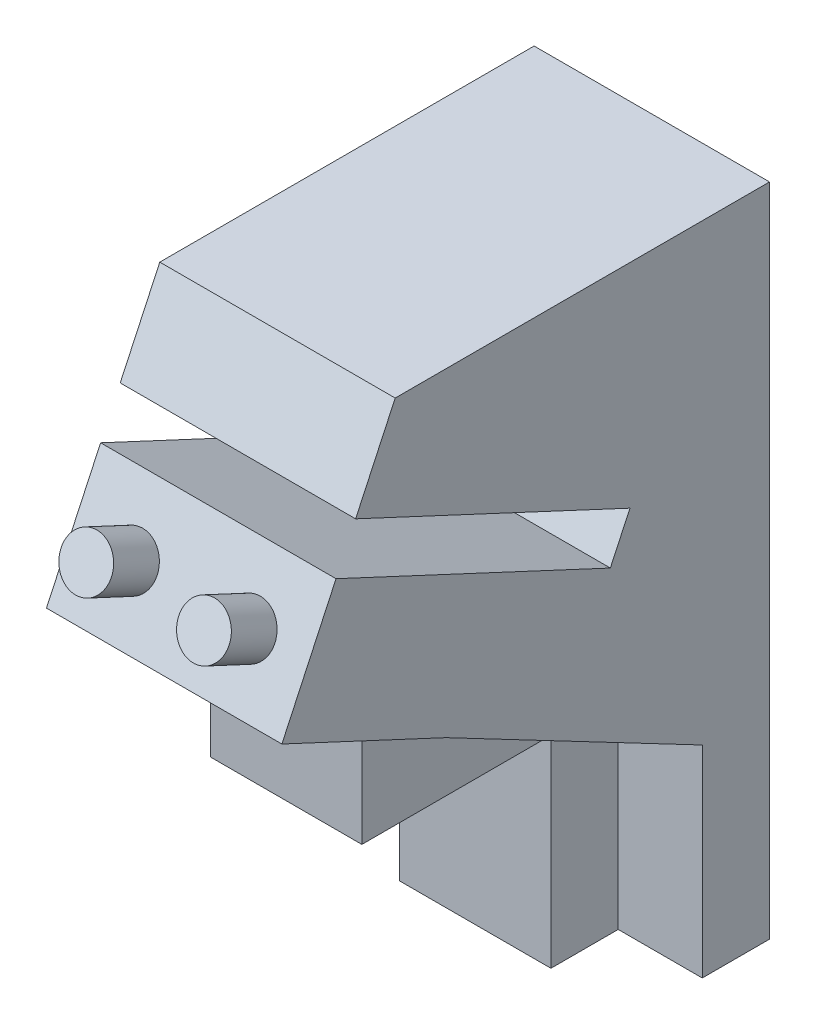
SolidWorks part; units mm, degrees
ref_plane "Front Plane" through (0, 0, 0) normal (1, 0, 0) x (0, 1, 0)
ref_plane "Top Plane" through (0, 0, 0) normal (0, 0, 1) x (0, 1, 0)
ref_plane "Right Plane" through (0, 0, 0) normal (0, 1, 0) x (-1, 0, 0)
sketch "Sketch2" plane through (0, 0, 0) normal (1, 0, 0) x (0, 1, 0)
  line L0 (0, 0) -> (78, 0)
  line L1 (0, 0) -> (0, 8)
  line L2 (0, 8) -> (25.784, 8) construction
  line L3 (25.784, 8) -> (49.0994, 58) construction
  line L4 (0, 8) -> (0, 16)
  line L5 (0, 16) -> (24, 16)
  line L6 (24, 16) -> (24, 38.4863)
  line L7 (24, 38.4863) -> (40, 38.4863)
  line L8 (49.0994, 58) -> (62.9093, 51.5603)
  line L9 (62.9093, 51.5603) -> (47.695, 18.9333)
  line L10 (47.695, 18.9333) -> (52.695, 16.6017)
  line L11 (52.695, 16.6017) -> (67.9093, 49.2288)
  line L12 (67.9093, 49.2288) -> (78, 44.5234) construction
  line L13 (78, 0) -> (78, 44.5234)
  line L14 (78, 44.5234) -> (67.9093, 49.2288)
  line L15 (40, 38.4863) -> (49.0994, 58)
  dimension "D1" = 78
  dimension "D2" = 8
  dimension "D3" = 50
  dimension "D4" = 65
  dimension "D5" = 8
  dimension "D6" = 24
  dimension "D7" = 16
  dimension "D8" = 90
  dimension "D9" = 90
  dimension "D10" = 36
  dimension "D11" = 5
  dimension "D12" = 36
  dimension "D13" = 90
extrude "Boss-Extrude1" add sketch "Sketch2" along normal blind 28
sketch "Sketch3" plane through (0, 0, 0) normal (1, 0, 0) x (0, 1, 0)
  line L0 (0, 8) -> (0, 16)
  line L1 (0, 16) -> (0, 0) construction
  line L2 (0, 16) -> (24, 16)
  line L3 (24, 16) -> (24, 38.4863)
  line L4 (24, 38.4863) -> (40, 38.4863)
  line L5 (40, 38.4863) -> (24, 8)
  line L6 (24, 8) -> (0, 8)
extrude "Cut-Extrude1" cut sketch "Sketch3" against normal blind 10 from surface at 28 starting at face at (28, 43.6923, 28.985)
ref_plane "Plane1" through (0, 35.2109, 75.5101) normal (0, 0.4226, 0.9063) x (1, 0, 0)
sketch "Sketch5" plane through (0, 35.2109, 75.5101) normal (0, 0.4226, 0.9063) x (1, 0, 0)
  line L0 (28, 19.9873) -> (0, 19.9873) construction
  line L1 (28, 35.2248) -> (28, 19.9873) construction
  line L2 (0, 35.2248) -> (0, 19.9873) construction
  circle A0 centre (7, 27.4873) radius 3
  circle A2 centre (21, 27.4873) radius 3
  dimension "D1" = 6
  dimension "D2" = 6
  dimension "D3" = 7.5
  dimension "D4" = 7.5
  dimension "D5" = 7
  dimension "D6" = 7
extrude "Boss-Extrude2" add sketch "Sketch5" along normal blind 6 from surface at -10 starting at face at (14, 56.0043, 54.7802)
